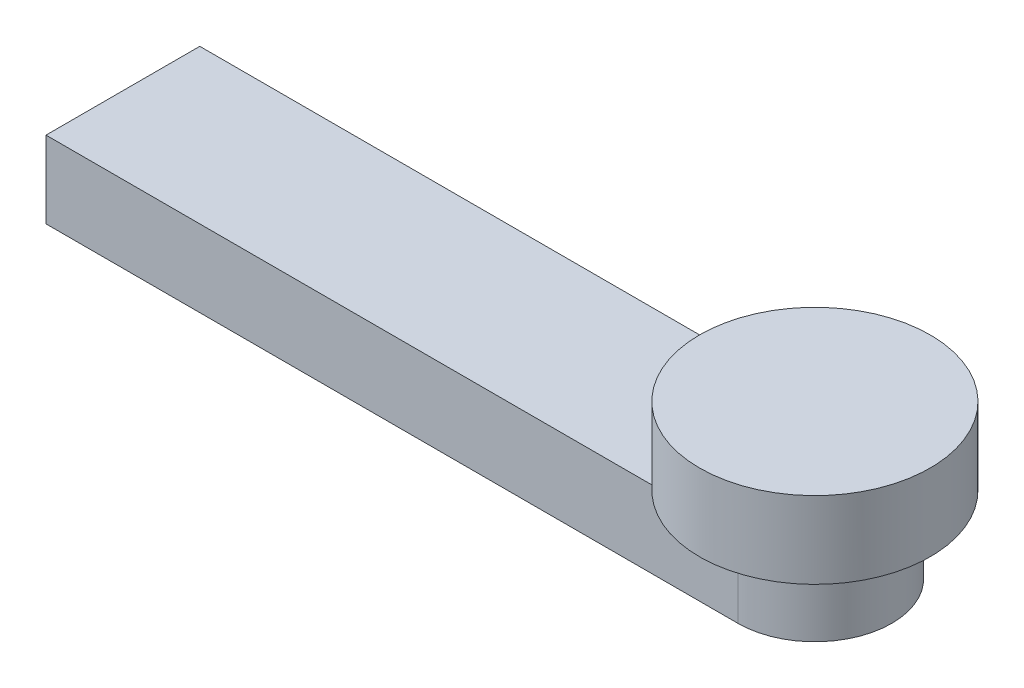
SolidWorks part; units mm, degrees
ref_plane "Front Plane" through (0, 0, 0) normal (0, 0, 1) x (1, 0, 0)
ref_plane "Top Plane" through (0, 0, 0) normal (0, 1, 0) x (1, 0, 0)
ref_plane "Right Plane" through (0, 0, 0) normal (1, 0, 0) x (0, 0, -1)
sketch "Sketch1" plane through (0, 0, 0) normal (0, 1, 0) x (1, 0, 0)
  line L1 (-45, 10) -> (45, 10)
  line L2 (-45, 10) -> (-45, -10)
  line L3 (-45, -10) -> (45, -10)
  line L5 (-45, 10) -> (45, -10) construction
  line L6 (-45, -10) -> (45, 10) construction
  arc A0 (45, -10) -> (45, 10) centre (45, 0) ccw
  point P0 (0, 0)
  dimension "D1" = 90
  dimension "D2" = 20
extrude "arm1" add sketch "Sketch1" along normal blind 10
sketch "Sketch3" plane through (0, 10, 0) normal (0, 1, 0) x (1, 0, 0)
  circle A0 centre (45, 0) radius 15
extrude "Boss-Extrude2" add sketch "Sketch3" along normal blind 10
